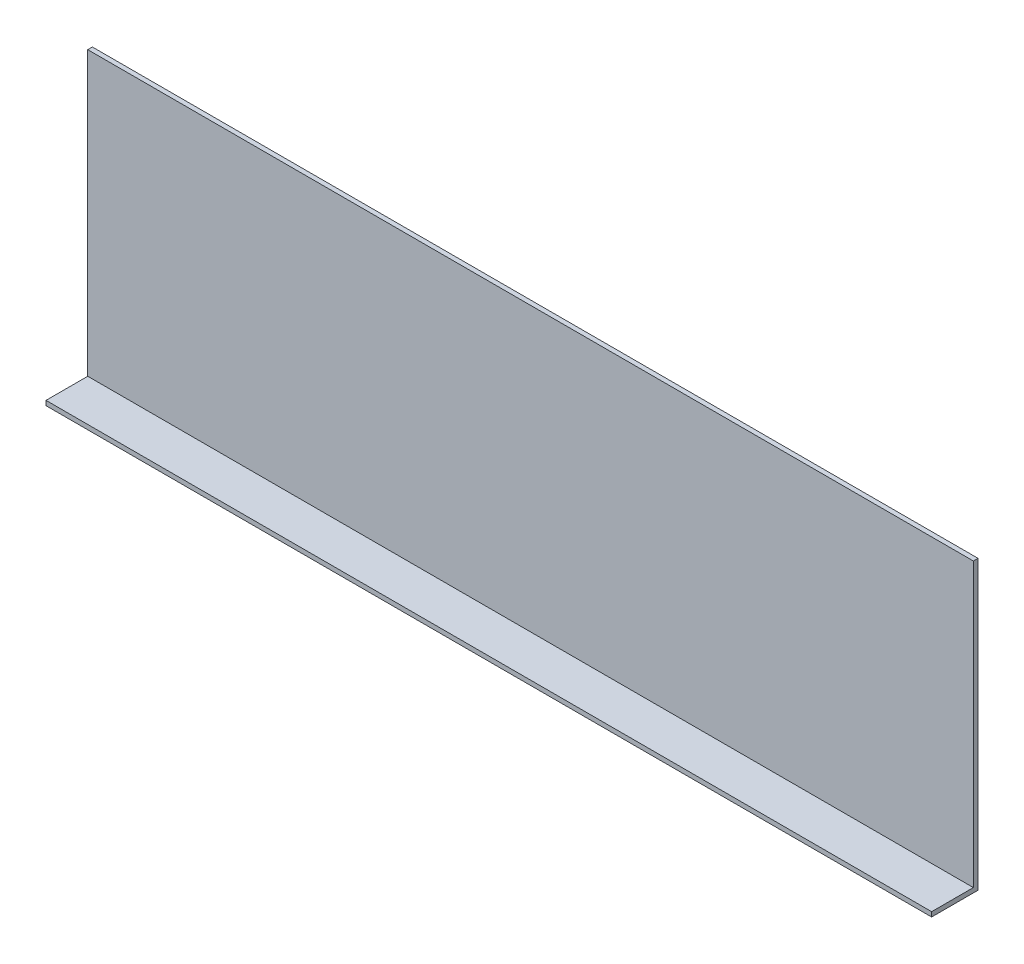
SolidWorks part; units mm, degrees
material "Acrylic (Medium-high impact)"
ref_plane "Front Plane" through (0, 0, 0) normal (0, 0, 1) x (1, 0, 0)
ref_plane "Top Plane" through (0, 0, 0) normal (0, 1, 0) x (1, 0, 0)
ref_plane "Right Plane" through (0, 0, 0) normal (1, 0, 0) x (0, 0, -1)
sketch "Sketch1" plane through (0, 0, 0) normal (0, 0, 1) x (1, 0, 0)
  line L1 (-477.5, -155) -> (477.5, -155)
  line L2 (-477.5, -155) -> (-477.5, 155)
  line L3 (-477.5, 155) -> (477.5, 155)
  line L4 (477.5, -155) -> (477.5, 155)
  line L5 (-477.5, -155) -> (477.5, 155) construction
  line L6 (-477.5, 155) -> (477.5, -155) construction
  point P0 (0, 0)
extrude "Boss-Extrude1" add sketch "Sketch1" along normal blind 5
sketch "Sketch2" plane through (0, 0, 0) normal (0, 0, 1) x (1, 0, 0)
  line L9 (477.5, -155) -> (477.5, 155) construction
  line L10 (-477.5, -155) -> (477.5, -155)
  line L18 (-477.5, -155) -> (-477.5, -150)
  line L19 (-477.5, -150) -> (477.5, -150)
  line L20 (477.5, -155) -> (477.5, -150)
extrude "Boss-Extrude2" add sketch "Sketch2" along normal blind 45 from surface at 5 starting at face at (0, 0, 5)
